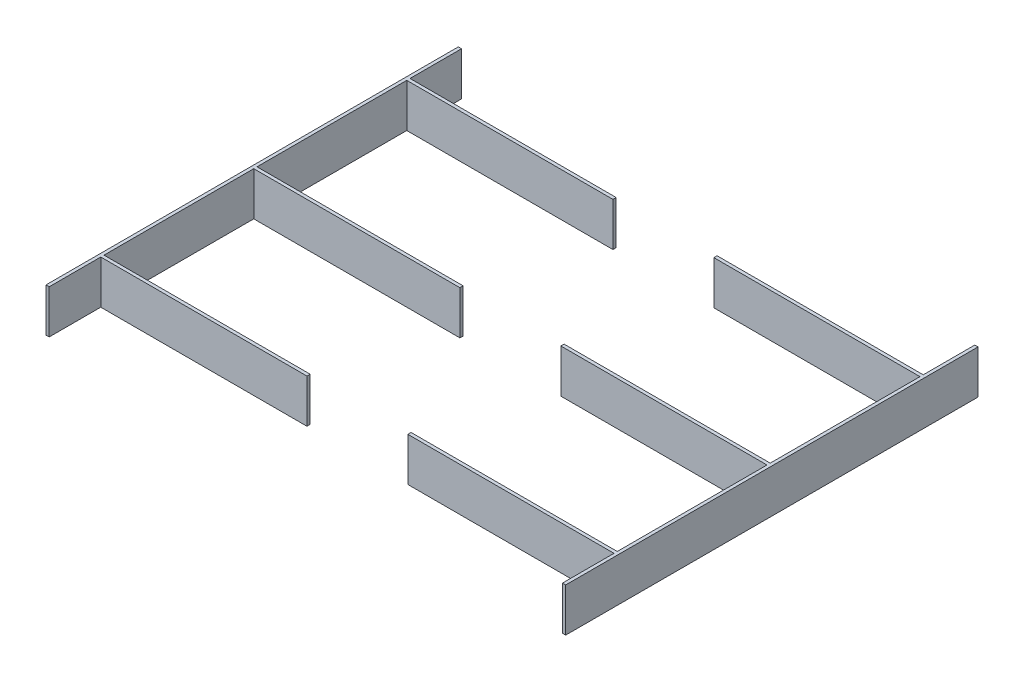
SolidWorks part; units mm, degrees
ref_plane "Front Plane" through (0, 0, 0) normal (0, 0, 1) x (1, 0, 0)
ref_plane "Top Plane" through (0, 0, 0) normal (0, 1, 0) x (1, 0, 0)
ref_plane "Right Plane" through (0, 0, 0) normal (1, 0, 0) x (0, 0, -1)
sketch "Sketch1" plane through (0, 0, 0) normal (0, 1, 0) x (1, 0, 0)
  line L0 (0, 519.5239) -> (0, -525.5046) construction
  line L1 (-1250.4709, 0) -> (317.072, 0) construction
  line L2 (-1536.7, 1219.2) -> (-1517.65, 1219.2)
  line L3 (-1536.7, 1219.2) -> (-1536.7, -1219.2)
  line L4 (-1536.7, -1219.2) -> (-1517.65, -1219.2)
  line L5 (-1517.65, 1219.2) -> (-1517.65, 914.4)
  line L6 (-1517.65, 895.35) -> (-298.45, 895.35)
  line L7 (-1517.65, -9.525) -> (-1517.65, -895.35)
  line L8 (-1517.65, 914.4) -> (-298.45, 914.4)
  line L9 (-298.45, 895.35) -> (-298.45, 914.4)
  line L10 (-1517.65, 9.525) -> (-298.45, 9.525)
  line L11 (-1517.65, -914.4) -> (-1517.65, -1219.2)
  line L12 (-1517.65, -9.525) -> (-298.45, -9.525)
  line L13 (-298.45, 9.525) -> (-298.45, -9.525)
  line L14 (-1517.65, -895.35) -> (-298.45, -895.35)
  line L16 (-1517.65, -914.4) -> (-298.45, -914.4)
  line L17 (-298.45, -895.35) -> (-298.45, -914.4)
  line L18 (298.45, -895.35) -> (298.45, -914.4)
  line L19 (1517.65, -914.4) -> (298.45, -914.4)
  line L20 (1517.65, -914.4) -> (1517.65, -1219.2)
  line L21 (1517.65, -895.35) -> (298.45, -895.35)
  line L22 (298.45, 9.525) -> (298.45, -9.525)
  line L23 (1517.65, -9.525) -> (298.45, -9.525)
  line L24 (1517.65, 895.35) -> (1517.65, 9.525)
  line L25 (1517.65, 9.525) -> (298.45, 9.525)
  line L26 (298.45, 895.35) -> (298.45, 914.4)
  line L27 (1517.65, 914.4) -> (298.45, 914.4)
  line L28 (1517.65, -9.525) -> (1517.65, -895.35)
  line L29 (1517.65, 895.35) -> (298.45, 895.35)
  line L30 (1517.65, 1219.2) -> (1517.65, 914.4)
  line L31 (1536.7, -1219.2) -> (1517.65, -1219.2)
  line L32 (1536.7, 1219.2) -> (1536.7, -1219.2)
  line L33 (1536.7, 1219.2) -> (1517.65, 1219.2)
  line L34 (-1517.65, 895.35) -> (-1517.65, 9.525)
  point P36 (298.45, 0)
  point P37 (1536.7, 0)
  dimension "D1" = 19.05
  dimension "D2" = 2438.4
  dimension "D3" = 1219.2
  dimension "D4" = 1536.7
  dimension "D5" = 304.8
extrude "Boss-Extrude1" add sketch "Sketch1" along normal blind 257.175 contours L8 L9 L6 L34 L10 L13 L12 L7 L14 L17 L16 L11 L4 L3 L2 L5 | L19 L18 L21 L28 L23 L22 L25 L24 L29 L26 L27 L30 L33 L32 L31 L20
